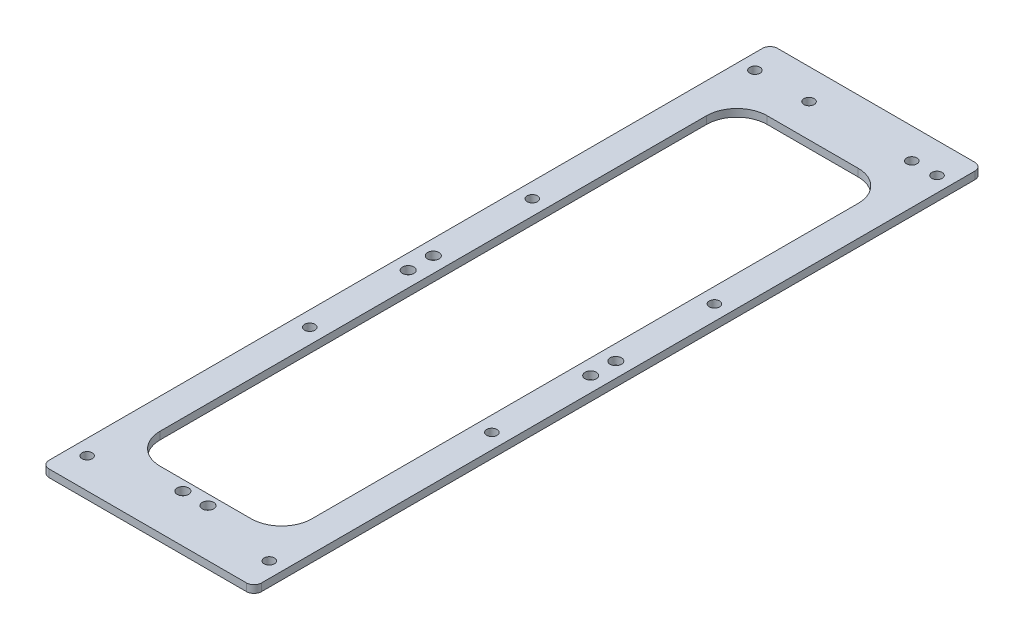
SolidWorks part; units mm, degrees
ref_plane "Front Plane" through (0, 0, 0) normal (0, 0, 1) x (1, 0, 0)
ref_plane "Top Plane" through (0, 0, 0) normal (0, 1, 0) x (1, 0, 0)
ref_plane "Right Plane" through (0, 0, 0) normal (1, 0, 0) x (0, 0, -1)
sketch "Sketch1" plane through (0, 0, 0) normal (0, 1, 0) x (1, 0, 0)
  line L1 (-44.45, 152.4) -> (44.45, 152.4)
  line L2 (-44.45, 152.4) -> (-44.45, -152.4)
  line L3 (-44.45, -152.4) -> (44.45, -152.4)
  line L4 (44.45, 152.4) -> (44.45, -152.4)
  line L14 (0, 0) -> (0, 187.5455) construction
  line L21 (0, 0) -> (44.45, 0) construction
  line L37 (-31.75, 125.8231) -> (31.75, 125.8231)
  line L40 (-31.75, 125.8231) -> (-31.75, -128.1769)
  line L43 (-31.75, -128.1769) -> (31.75, -128.1769)
  line L46 (31.75, 125.8231) -> (31.75, -128.1769)
  point P4 (0, 152.4)
  point P6 (-44.45, 0)
  dimension "D4" = 254
  dimension "D2" = 88.9
  dimension "D3" = 304.8
  dimension "D6" = 12.7
  dimension "D12" = 12.7
extrude "Boss-Extrude1" add sketch "Sketch1" along normal blind 3.175
sketch "Sketch7" plane through (0, 3.175, 0) normal (0, 1, 0) x (1, 0, 0)
  line L1 (-44.45, 152.4) -> (-44.45, -152.4) construction
  line L2 (0, 0) -> (0, 246.0772) construction
  line L3 (0, 0) -> (301.4392, 0) construction
  line L4 (44.45, 152.4) -> (-44.45, 152.4) construction
  circle A0 centre (-38.1, 139.7363) radius 2.159
  circle A10 centre (38.1, 139.7363) radius 2.159
  circle A13 centre (-38.1, 46.6029) radius 2.159
  circle A14 centre (-38.1, -46.5305) radius 2.159
  circle A15 centre (-38.1, -139.664) radius 2.159
  circle A16 centre (38.1, 46.6021) radius 2.159
  circle A17 centre (38.1, -46.5321) radius 2.159
  circle A18 centre (38.1, -139.6662) radius 2.159
  dimension "D1" = 4.318
  dimension "D3" = 6.35
  dimension "D4" = 4
  dimension "D5" = 4
  dimension "D8" = 12.6637
extrude "Cut-Extrude2" cut sketch "Sketch7" against normal through all
fillet "Fillet1" radius 12.7 4 edges at (31.75, 1.5875, 128.1769) (-31.75, 1.5875, 128.1769) (-31.75, 1.5875, -125.8231) (31.75, 1.5875, -125.8231)
sketch "Sketch8" [suppressed] plane through (0, 3.175, 0) normal (0, 1, 0) x (1, 0, 0)
  line L0 (184.15, 139.7) -> (-184.15, 139.7) construction
  line L1 (0, 139.7) -> (0, 110.7046) construction
  circle A0 centre (-15.7442, 133.35) radius 2.159
  circle A1 centre (15.7442, 133.35) radius 2.159
  dimension "D5" = 4.318
  dimension "D6" = 4.318
  dimension "D1" = 6.35
  dimension "D2" = 6.35
  dimension "D3" = 31.4884
  dimension "D4" = 15.7442
fillet "Fillet3" radius 3.175 4 edges at (-44.45, 1.5875, 152.4) (44.45, 1.5875, 152.4) (44.45, 1.5875, -152.4) (-44.45, 1.5875, -152.4)
sketch "Sketch9" plane through (0, 3.175, 0) normal (0, 1, 0) x (1, 0, 0)
  line L1 (44.45, -149.225) -> (44.45, 149.225) construction
  line L2 (41.275, 152.4) -> (-41.275, 152.4) construction
  circle A0 centre (-15.4178, 139.7) radius 2.159
  circle A1 centre (27.5844, 139.7) radius 2.159
  dimension "D1" = 4.318
  dimension "D2" = 4.318
  dimension "D5" = 12.7
  dimension "D6" = 12.7
  dimension "D3" = 59.8678
  dimension "D4" = 16.8656
extrude "Cut-Extrude4" cut sketch "Sketch9" against normal through all contours A0 | A1
sketch "Sketch10" plane through (0, 3.175, 0) normal (0, 1, 0) x (1, 0, 0)
  line L0 (0, 0) -> (0, -287.9287) construction
  line L1 (-19.05, -128.1769) -> (19.05, -128.1769) construction
  circle A0 centre (-5.2462, -132.4582) radius 2.3812
  circle A2 centre (5.2462, -132.4582) radius 2.3813
  dimension "D1" = 10.4925
  dimension "D2" = 4.2813
extrude "Sonar Holes" cut sketch "Sketch10" against normal through all
sketch "Sketch11" plane through (0, 3.175, 0) normal (0, 1, 0) x (1, 0, 0)
  line L0 (0, 0) -> (-173.0616, 0) construction
  line L1 (0, 0) -> (0, -174.5172) construction
  circle A0 centre (-38.1811, 5.2462) radius 2.3812
  circle A1 centre (-38.1811, -5.2463) radius 2.3812
  circle A2 centre (38.1811, -5.2463) radius 2.3812
  circle A3 centre (38.1811, 5.2462) radius 2.3812
  dimension "D1" = 10.4925
extrude "Sonar Holes 2: Electric Boogaloo" cut sketch "Sketch11" against normal through all
